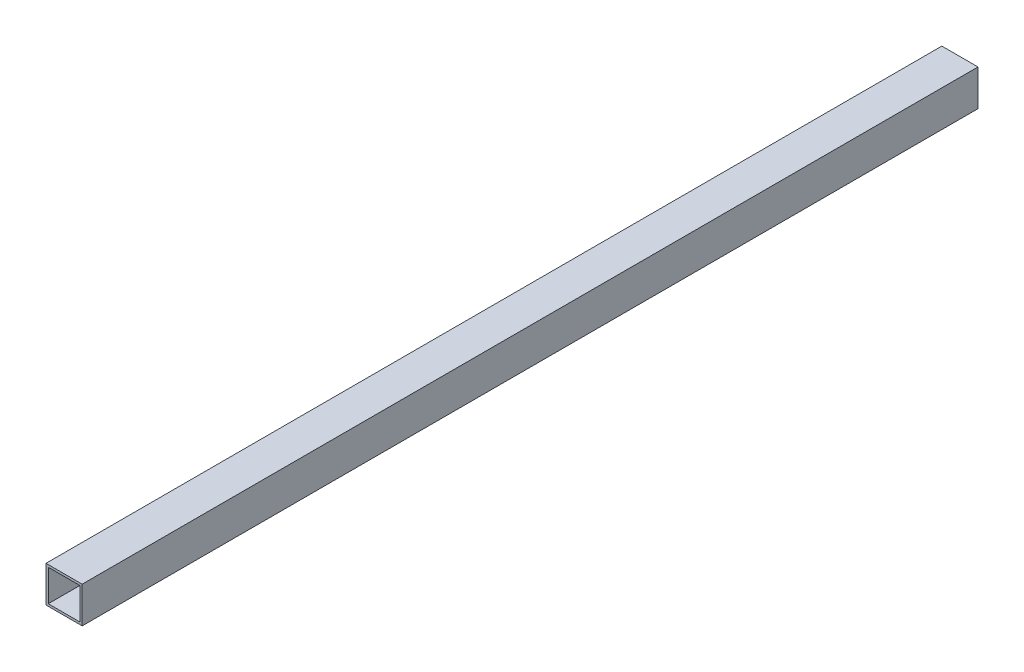
SolidWorks part; units mm, degrees
material "Acrylic (Medium-high impact)"
ref_plane "Front Plane" through (0, 0, 0) normal (0, 0, 1) x (1, 0, 0)
ref_plane "Top Plane" through (0, 0, 0) normal (0, 1, 0) x (1, 0, 0)
ref_plane "Right Plane" through (0, 0, 0) normal (1, 0, 0) x (0, 0, -1)
sketch "Sketch1" plane through (0, 0, 0) normal (0, 0, 1) x (1, 0, 0)
  line L1 (12.7, 12.7) -> (-12.7, 12.7)
  line L2 (12.7, 12.7) -> (12.7, -12.7)
  line L3 (12.7, -12.7) -> (-12.7, -12.7)
  line L4 (-12.7, 12.7) -> (-12.7, -12.7)
  line L5 (12.7, 12.7) -> (-12.7, -12.7) construction
  line L6 (12.7, -12.7) -> (-12.7, 12.7) construction
  line L7 (11.1125, 11.1125) -> (-11.1125, 11.1125)
  line L8 (11.1125, 11.1125) -> (11.1125, -11.1125)
  line L9 (11.1125, -11.1125) -> (-11.1125, -11.1125)
  line L10 (-11.1125, 11.1125) -> (-11.1125, -11.1125)
  line L11 (11.1125, 11.1125) -> (-11.1125, -11.1125) construction
  line L12 (11.1125, -11.1125) -> (-11.1125, 11.1125) construction
  point P0 (0, 0)
  point P6 (0, 0)
  dimension "D1" = 1.5875
  dimension "D2" = 25.4
extrude "Boss-Extrude1" add sketch "Sketch1" along normal mid plane 629.2794
